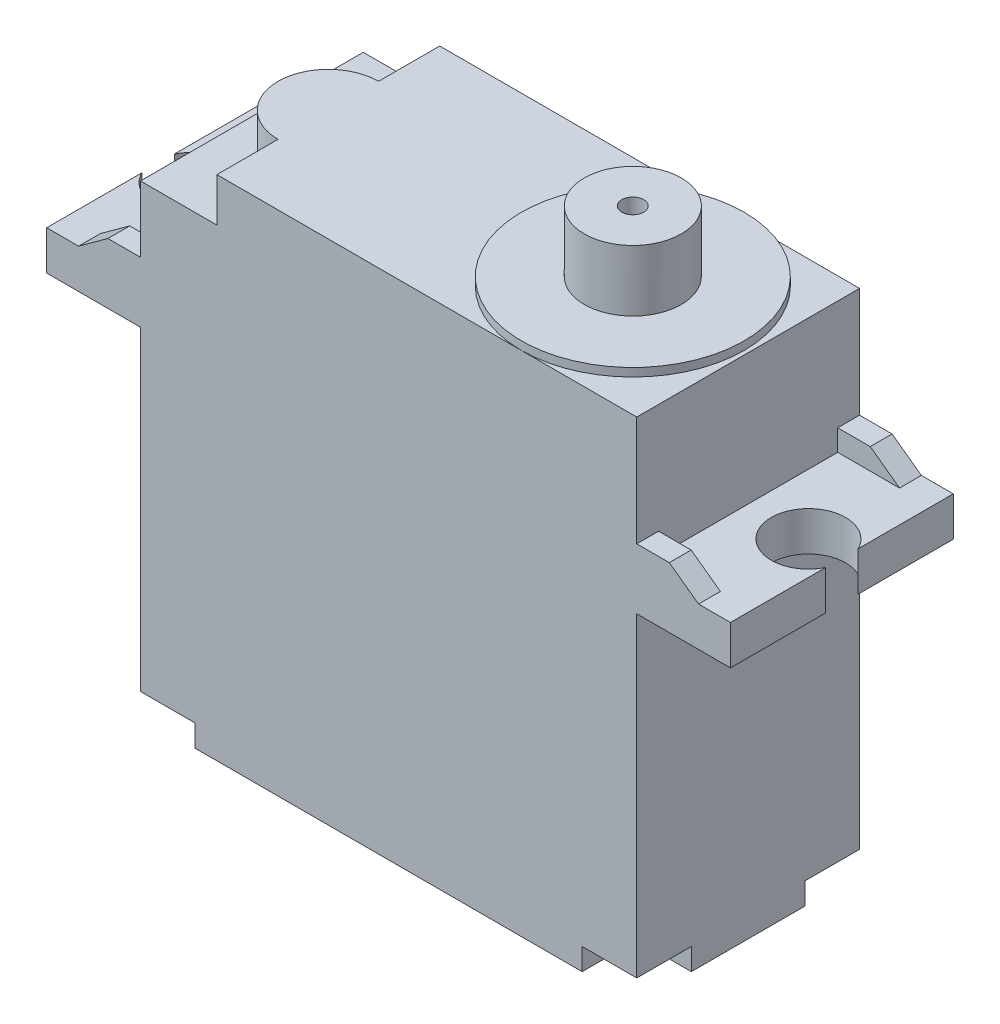
SolidWorks part; units mm, degrees
ref_plane "Front Plane" through (0, 0, 0) normal (0, 0, 1) x (1, 0, 0)
ref_plane "Top Plane" through (0, 0, 0) normal (0, 1, 0) x (1, 0, 0)
ref_plane "Right Plane" through (0, 0, 0) normal (1, 0, 0) x (0, 0, -1)
sketch "Sketch1" plane through (0, 0, 0) normal (0, 1, 0) x (1, 0, 0)
  circle A0 centre (0, 0) radius 2.8194
  dimension "D1" = 5.6388
extrude "Boss-Extrude1" add sketch "Sketch1" along normal blind 3.556
sketch "Sketch2" plane through (0, 0, 0) normal (0, -1, 0) x (-1, 0, 0)
  circle A0 centre (0, 0) radius 6.477
  dimension "D1" = 12.954
extrude "Boss-Extrude2" add sketch "Sketch2" along normal blind 0.4826
sketch "Sketch3" plane through (0, -0.4826, 0) normal (0, -1, 0) x (-1, 0, 0)
  line L0 (0, -6.477) -> (-6.7056, -6.477) construction
  line L1 (-6.7056, -6.477) -> (-6.7056, 6.477) construction
  line L2 (-6.7056, 6.477) -> (0, 6.477) construction
  line L4 (-6.7056, -6.477) -> (22.1488, -6.477)
  line L5 (-6.7056, -6.477) -> (-6.7056, 6.477)
  line L6 (-6.7056, 6.477) -> (22.1488, 6.477)
  line L7 (22.1488, -6.477) -> (22.1488, 6.477)
  circle A0 centre (0, 0) radius 6.477 construction
  dimension "D1" = 28.8544
  dimension "D2" = 6.7056
extrude "Boss-Extrude3" add sketch "Sketch3" along normal blind 29.5148
sketch "Sketch4" plane through (0, 3.556, 0) normal (0, 1, 0) x (1, 0, 0)
  circle A0 centre (0, 0) radius 0.635
  dimension "D1" = 1.27
extrude "Cut-Extrude1" cut sketch "Sketch4" against normal blind 3.937
sketch "Sketch5" plane through (6.7056, 0, 0) normal (1, 0, 0) x (0, 0, -1)
  line L0 (-6.477, -29.9974) -> (-6.477, -0.4826) construction
  line L1 (-6.477, -8.1026) -> (6.477, -8.1026)
  line L2 (-6.477, -8.1026) -> (-6.477, -10.3886)
  line L3 (-6.477, -10.3886) -> (6.477, -10.3886)
  line L4 (6.477, -8.1026) -> (6.477, -10.3886)
  line L5 (6.477, -29.9974) -> (6.477, -0.4826) construction
  line L6 (6.477, -0.4826) -> (-6.477, -0.4826) construction
  line L7 (6.477, -29.9974) -> (-6.477, -29.9974) construction
  dimension "D1" = 7.62
  dimension "D2" = 19.6088
extrude "Boss-Extrude4" add sketch "Sketch5" along normal blind 5.4483
sketch "Sketch6" plane through (0, 0, 6.477) normal (0, 0, 1) x (1, 0, 0)
  line L0 (6.7056, -8.1026) -> (10.2997, -8.1026)
  line L1 (12.1539, -8.1026) -> (6.7056, -8.1026) construction
  line L2 (10.2997, -8.1026) -> (8.5979, -6.8665)
  line L3 (8.5979, -6.8665) -> (6.7056, -6.8665)
  line L4 (6.7056, -8.1026) -> (6.7056, -0.4826) construction
  line L5 (6.7056, -6.8665) -> (6.7056, -8.1026)
  line L7 (12.1539, -8.1026) -> (12.1539, -10.3886) construction
  dimension "D1" = 1.2361
  dimension "D2" = 1.8542
  dimension "D3" = 3.556
extrude "Boss-Extrude5" add sketch "Sketch6" against normal blind 1.27
mirror "Mirror1" about plane through (0, 0, 0) normal (0, 0, 1) of "Boss-Extrude5"
ref_plane "Plane1" through (-7.7216, 0, 0) normal (1, 0, 0) x (0, 0, -1)
sketch "Sketch7" plane through (0, -8.1026, 0) normal (0, 1, 0) x (1, 0, 0)
  line L0 (12.1539, 0) -> (6.7056, 0) construction
  line L1 (12.1539, 6.477) -> (12.1539, -6.477) construction
  line L2 (6.7056, 5.207) -> (6.7056, -5.207) construction
  circle A0 centre (10.2108, 0) radius 2.159
  circle A1 centre (0, 0) radius 0.635 construction
  dimension "D2" = 4.318
  dimension "D1" = 10.2108
extrude "Cut-Extrude2" cut sketch "Sketch7" against normal through all
mirror "Mirror3" about plane through (-7.7216, 0, 0) normal (1, 0, 0) of "Boss-Extrude4", "Boss-Extrude5", "Mirror1", "Cut-Extrude2"
sketch "Sketch9" plane through (0, -0.4826, 0) normal (0, 1, 0) x (1, 0, 0)
  line L0 (-22.1488, 6.477) -> (0, 6.477) construction
  line L1 (-22.1488, -6.477) -> (-17.7038, -6.477)
  line L2 (-22.1488, -6.477) -> (-22.1488, 6.477)
  line L3 (-22.1488, 6.477) -> (-17.7038, 6.477)
  line L4 (-17.7038, -6.477) -> (-17.7038, 6.477)
  circle A0 centre (-17.7038, 0) radius 2.921
  line M2 (-22.1488, -6.477) -> (0, -6.477)
  line M4 (0, 6.477) -> (-22.1488, 6.477)
  line M5 (-22.1488, 6.477) -> (-22.1488, -6.477)
  dimension "D1" = 5.842
  dimension "D2" = 4.445
extrude "Cut-Extrude3" cut sketch "Sketch9" against normal blind 2.54 contours A0 L4 M4 M5 M2
sketch "Sketch10" plane through (0, -29.9974, 0) normal (0, -1, 0) x (-1, 0, 0)
  line L0 (20.5613, 4.8895) -> (22.1488, 4.8895) construction
  line L1 (22.1488, -6.477) -> (22.1488, 6.477) construction
  line L2 (20.5613, 4.8895) -> (20.5613, 6.477) construction
  line L3 (22.1488, 6.477) -> (-6.7056, 6.477) construction
  line L4 (20.5613, 6.477) -> (22.1488, 6.477)
  line L5 (22.1488, 6.477) -> (22.1488, 4.8895)
  line L6 (20.5613, 3.302) -> (22.1488, 3.302)
  line L7 (22.1488, 3.302) -> (22.1488, 4.8895)
  line L8 (18.9738, 4.8895) -> (18.9738, 6.477)
  line L9 (18.9738, 6.477) -> (22.1488, 6.477)
  line L10 (22.1488, 3.302) -> (20.5613, 3.302)
  circle A0 centre (20.5613, 4.8895) radius 1.5875
  line M5 (22.1488, -6.477) -> (22.1488, 6.477)
  line M6 (22.1488, 6.477) -> (-6.7056, 6.477)
  dimension "D1" = 3.175
  dimension "D2" = 1.5875
extrude "Cut-Extrude4" cut sketch "Sketch10" against normal blind 1.27 contours A0 | A0 M5 M6 | A0 L8 M6 | A0 L6 M5
mirror "Mirror4" about plane through (0, 0, 0) normal (0, 0, 1) of "Cut-Extrude4"
mirror "Mirror5" about plane through (-7.7216, 0, 0) normal (1, 0, 0) of "Mirror4", "Cut-Extrude4"
